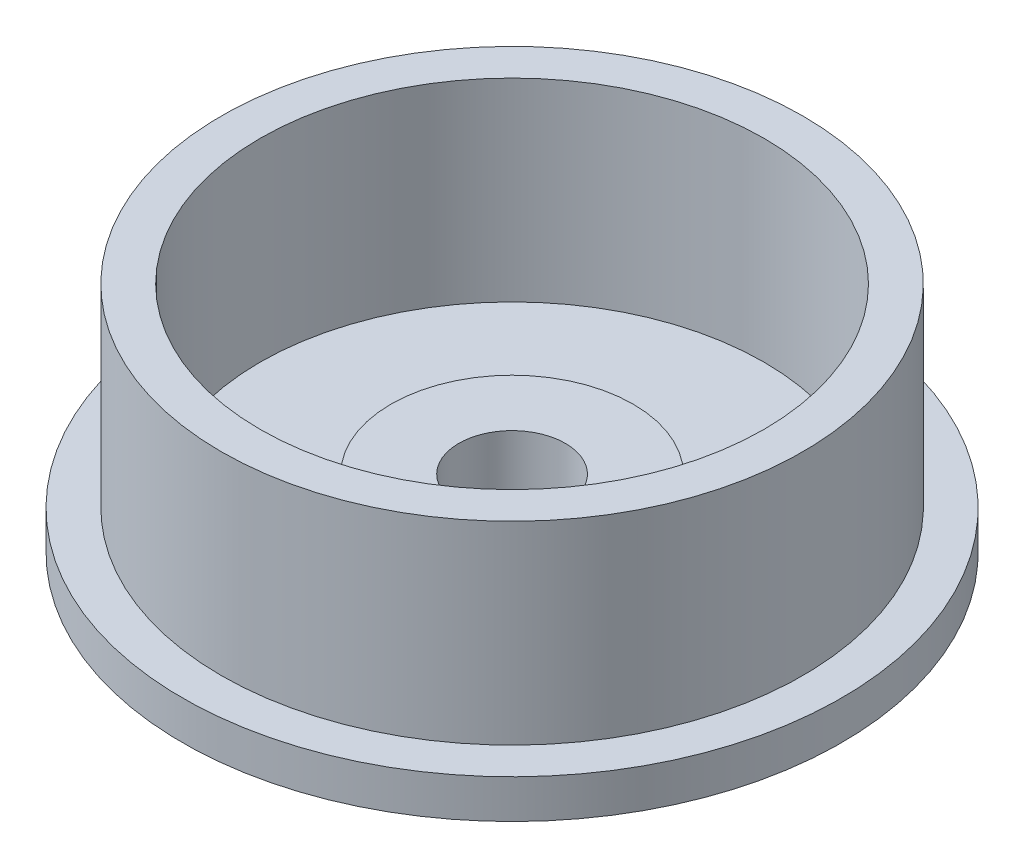
SolidWorks part; units mm, degrees
ref_plane "Front Plane" through (0, 0, 0) normal (0, 0, 1) x (1, 0, 0)
ref_plane "Top Plane" through (0, 0, 0) normal (0, 1, 0) x (1, 0, 0)
ref_plane "Right Plane" through (0, 0, 0) normal (1, 0, 0) x (0, 0, -1)
sketch "Sketch2" plane through (0, 0, 0) normal (0, 1, 0) x (1, 0, 0)
  circle A0 centre (0, 0) radius 15
  dimension "D2" = 30
extrude "Boss-Extrude1" add sketch "Sketch2" along normal blind 12
shell "Shell1" thickness 2
sketch "Sketch4" plane through (0, 0, 0) normal (0, -1, 0) x (1, 0, 0)
  circle A0 centre (0, 0) radius 2.75
  dimension "D1" = 5.5
extrude "Cut-Extrude1" cut sketch "Sketch4" against normal through all
sketch "Sketch5" plane through (0, 0, 0) normal (0, -1, 0) x (1, 0, 0)
  circle A0 centre (0, 0) radius 17
  circle A1 centre (0, 0) radius 15
  circle A2 centre (0, 0) radius 15
  dimension "D2" = 2
  dimension "D1" = 0
extrude "Boss-Extrude3" add sketch "Sketch5" against normal blind 2
sketch "Sketch7" plane through (0, 0, 0) normal (0, -1, 0) x (1, 0, 0)
  circle A0 centre (0, 0) radius 4.25
  circle A1 centre (0, 0) radius 2.75 construction
  circle A2 centre (0, 0) radius 2.75
  dimension "D1" = 1.5
extrude "Boss-Extrude5" add sketch "Sketch7" along normal blind 4
sketch "Sketch6" plane through (0, 2, 0) normal (0, 1, 0) x (1, 0, 0)
  circle A0 centre (0, 0) radius 2.75
  circle A1 centre (0, 0) radius 6.25
  circle A4 centre (0, 0) radius 2.75 construction
  dimension "D1" = 3.5
extrude "Boss-Extrude4" add sketch "Sketch6" along normal offset from surface (1.5 mm away) 7.5 up to face at (0, -4, -4.25)
